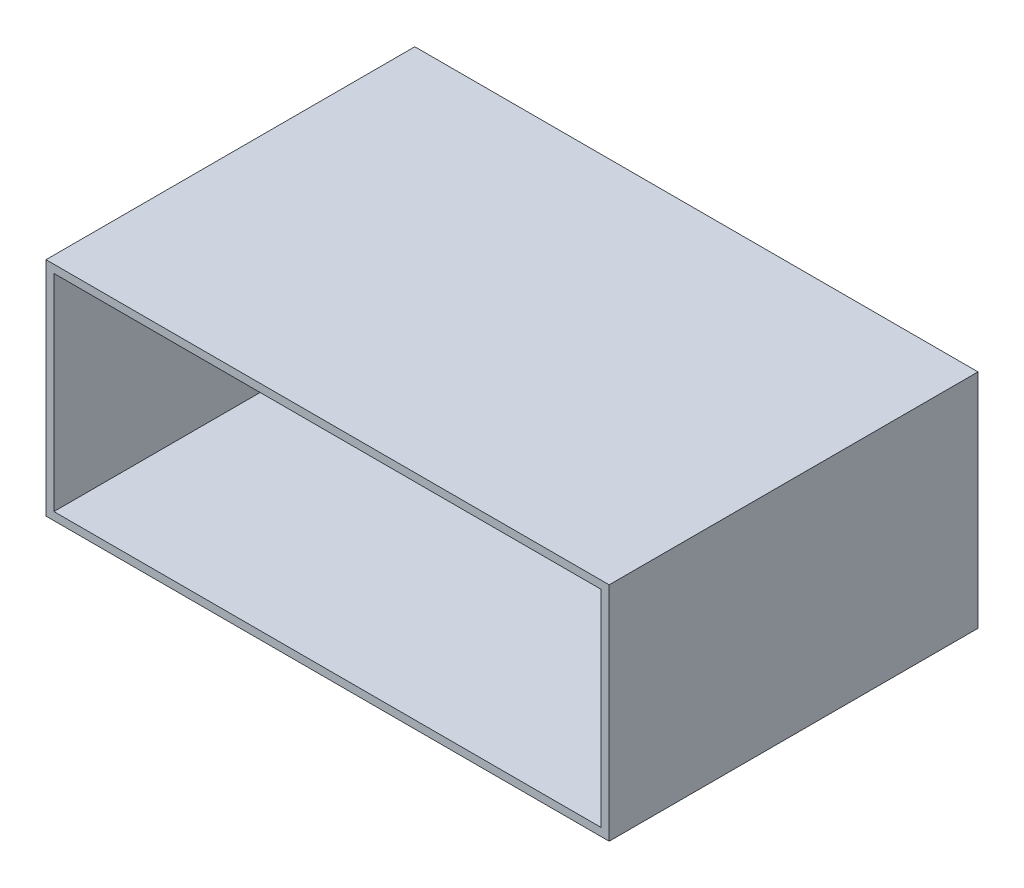
SolidWorks part; units mm, degrees
ref_plane "Front Plane" through (0, 0, 0) normal (0, 0, 1) x (1, 0, 0)
ref_plane "Top Plane" through (0, 0, 0) normal (0, 1, 0) x (1, 0, 0)
ref_plane "Right Plane" through (0, 0, 0) normal (1, 0, 0) x (0, 0, -1)
sketch "Sketch1" plane through (0, 0, 0) normal (0, 0, 1) x (1, 0, 0)
  line L1 (0, 0) -> (142, 0)
  line L2 (0, 0) -> (0, 56)
  line L3 (0, 56) -> (142, 56)
  line L4 (142, 0) -> (142, 56)
  line L6 (2, 2) -> (140, 2)
  line L7 (2, 2) -> (2, 54)
  line L8 (2, 54) -> (140, 54)
  line L9 (140, 2) -> (140, 54)
  dimension "D1" = 2
  dimension "D2" = 140
  dimension "D3" = 142
  dimension "D4" = 2
  dimension "D5" = 54
  dimension "D6" = 56
extrude "Profile" add sketch "Sketch1" along normal blind 93
sketch "Sketch2" plane through (0, 0, 0) normal (0, 0, 1) x (1, 0, 0)
  line L1 (2, 2) -> (140, 2)
  line L2 (2, 2) -> (2, 54)
  line L3 (2, 54) -> (140, 54)
  line L4 (140, 2) -> (140, 54)
  dimension "D1" = 138
  dimension "D2" = 52
extrude "Back" add sketch "Sketch2" along normal blind 2
equation "\"Profile_Depth\"= 93mm"
equation "\"D1@Profile\" = \"Profile_Depth\""
equation "\"Profile_Sketch_1\"= 2mm"
equation "\"D1@Sketch1\" = \"Profile_Sketch_1\""
equation "\"Profile_Sketch_2\"= 140mm"
equation "\"D2@Sketch1\" = \"Profile_Sketch_2\""
equation "\"Profile_Sketch_3\"= 142mm"
equation "\"D3@Sketch1\" = \"Profile_Sketch_3\""
equation "\"Profile_Sketch_4\"= 2mm"
equation "\"D4@Sketch1\" = \"Profile_Sketch_4\""
equation "\"Profile_Sketch_5\"= 54mm"
equation "\"D5@Sketch1\" = \"Profile_Sketch_5\""
equation "\"Profile_Sketch_6\"= 56mm"
equation "\"D6@Sketch1\" = \"Profile_Sketch_6\""
equation "\"Back_Depth\"= 2mm"
equation "\"D1@Back\" = \"Back_Depth\""
equation "\"Back_Sketch_1\"= 138mm"
equation "\"D1@Sketch2\" = \"Back_Sketch_1\""
equation "\"Back_Sketch_2\"= 52mm"
equation "\"D2@Sketch2\" = \"Back_Sketch_2\""
equation "\"EnvelopeWidth\"= 142mm"
equation "\"EnvelopeHeight\"= 56mm"
